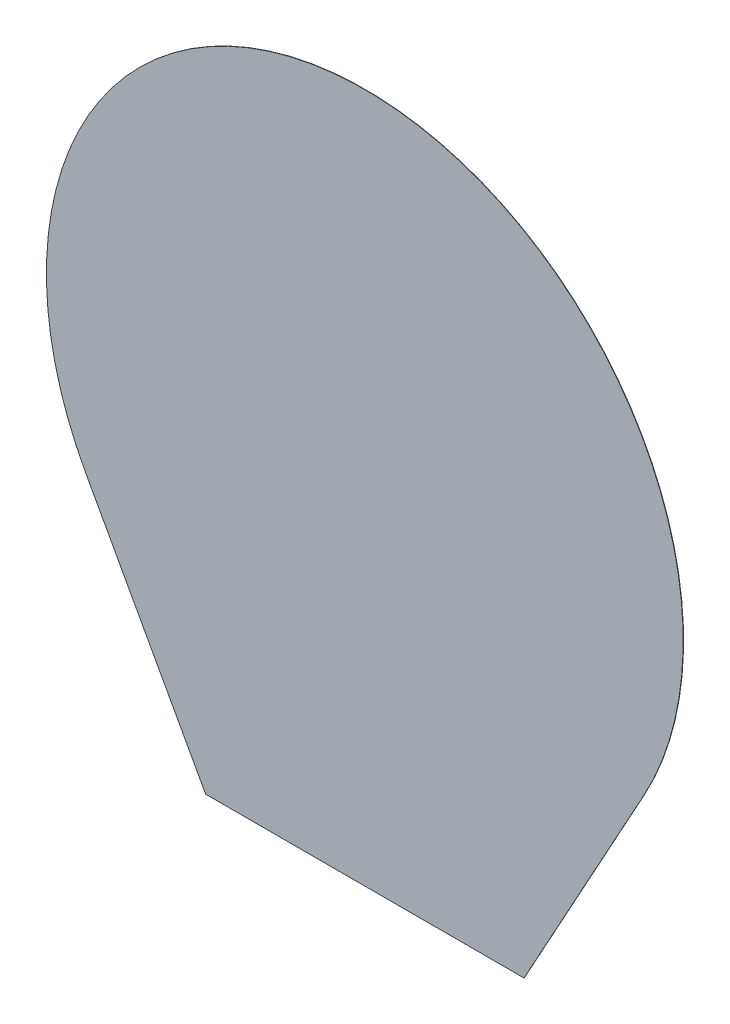
SolidWorks part; units mm, degrees
ref_plane "Plano frontal" through (0, 0, 0) normal (0, 0, 1) x (1, 0, 0)
ref_plane "Plano superior" through (0, 0, 0) normal (0, 1, 0) x (1, 0, 0)
ref_plane "Plano direito" through (0, 0, 0) normal (1, 0, 0) x (0, 0, -1)
sketch "Sketch1" plane through (0, 0, 0) normal (0, 0, 1) x (1, 0, 0)
  line L10 (-15, -35) -> (15, -35)
  line L13 (15, -25.6868) -> (15, -25.9808)
  line L14 (-15, -35) -> (-26.2929, -14.4459)
  line L15 (15, -35) -> (26.2929, -14.4459)
  arc A2 (26.2929, -14.4459) -> (-26.2929, -14.4459) centre (0, 0) ccw
  point P11 (0, -35)
  dimension "D7" = 60
  dimension "D5" = 30
extrude "Boss-Extrude1" add sketch "Sketch1" along normal blind 0.0356
